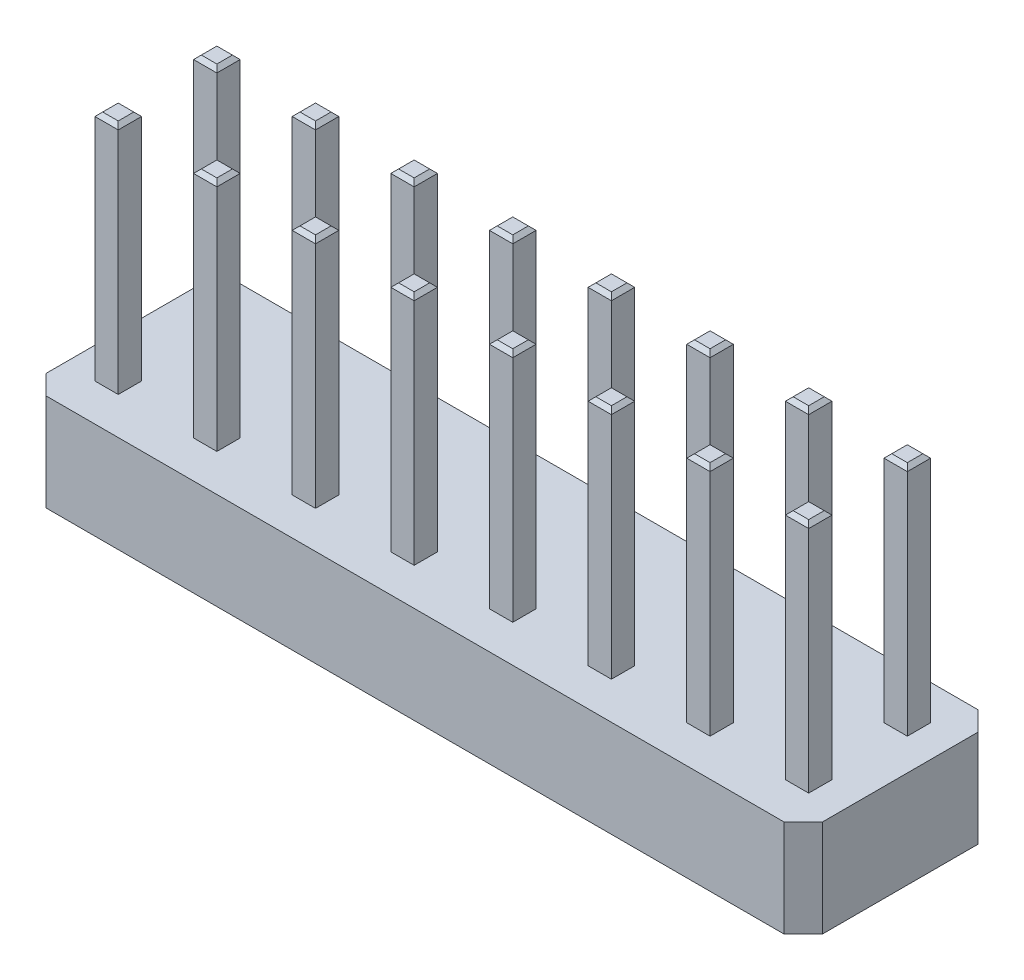
SolidWorks part; units mm, degrees
ref_plane "Plan de face" through (0, 0, 0) normal (0, 0, 1) x (1, 0, 0)
ref_plane "Plan de dessus" through (0, 0, 0) normal (0, 1, 0) x (1, 0, 0)
ref_plane "Plan de droite" through (0, 0, 0) normal (1, 0, 0) x (0, 0, -1)
sketch "Esquisse1" plane through (0, 0, 0) normal (0, 1, 0) x (1, 0, 0)
  line L1 (0, 0) -> (20, 0)
  line L2 (0, 0) -> (0, -5)
  line L3 (0, -5) -> (20, -5)
  line L4 (20, 0) -> (20, -5)
  dimension "D1" = 20
  dimension "D2" = 5
extrude "Boss.-Extru.1" add sketch "Esquisse1" along normal blind 2.5
sketch "Esquisse2" plane through (0, 2.5, 0) normal (0, 1, 0) x (1, 0, 0)
  line L0 (20, 0) -> (0, 0) construction
  line L1 (0.8, -0.9) -> (1.4, -0.9)
  line L2 (0.8, -0.9) -> (0.8, -1.5)
  line L3 (0.8, -1.5) -> (1.4, -1.5)
  line L4 (1.4, -0.9) -> (1.4, -1.5)
  line L5 (0.8, -3.44) -> (1.4, -3.44)
  line L6 (0.8, -3.44) -> (0.8, -4.04)
  line L7 (0.8, -4.04) -> (1.4, -4.04)
  line L8 (1.4, -3.44) -> (1.4, -4.04)
  line L17 (3.34, -0.9) -> (3.94, -0.9)
  line L18 (0, 0) -> (0, -5) construction
  line L19 (3.34, -0.9) -> (3.34, -1.5)
  line L20 (3.34, -1.5) -> (3.94, -1.5)
  line L21 (3.94, -0.9) -> (3.94, -1.5)
  line L22 (3.34, -3.44) -> (3.94, -3.44)
  line L23 (3.34, -3.44) -> (3.34, -4.04)
  line L24 (3.34, -4.04) -> (3.94, -4.04)
  line L25 (3.94, -3.44) -> (3.94, -4.04)
  line L26 (5.88, -0.9) -> (6.48, -0.9)
  line L27 (5.88, -0.9) -> (5.88, -1.5)
  line L28 (5.88, -1.5) -> (6.48, -1.5)
  line L29 (6.48, -0.9) -> (6.48, -1.5)
  line L30 (5.88, -3.44) -> (6.48, -3.44)
  line L31 (5.88, -3.44) -> (5.88, -4.04)
  line L32 (5.88, -4.04) -> (6.48, -4.04)
  line L33 (6.48, -3.44) -> (6.48, -4.04)
  line L34 (8.42, -0.9) -> (9.02, -0.9)
  line L35 (8.42, -0.9) -> (8.42, -1.5)
  line L36 (8.42, -1.5) -> (9.02, -1.5)
  line L37 (9.02, -0.9) -> (9.02, -1.5)
  line L38 (8.42, -3.44) -> (9.02, -3.44)
  line L39 (8.42, -3.44) -> (8.42, -4.04)
  line L40 (8.42, -4.04) -> (9.02, -4.04)
  line L41 (9.02, -3.44) -> (9.02, -4.04)
  line L42 (10.96, -0.9) -> (11.56, -0.9)
  line L43 (10.96, -0.9) -> (10.96, -1.5)
  line L44 (10.96, -1.5) -> (11.56, -1.5)
  line L45 (11.56, -0.9) -> (11.56, -1.5)
  line L46 (10.96, -3.44) -> (11.56, -3.44)
  line L47 (10.96, -3.44) -> (10.96, -4.04)
  line L48 (10.96, -4.04) -> (11.56, -4.04)
  line L49 (11.56, -3.44) -> (11.56, -4.04)
  line L50 (13.5, -0.9) -> (14.1, -0.9)
  line L51 (13.5, -0.9) -> (13.5, -1.5)
  line L52 (13.5, -1.5) -> (14.1, -1.5)
  line L53 (14.1, -0.9) -> (14.1, -1.5)
  line L54 (13.5, -3.44) -> (14.1, -3.44)
  line L55 (13.5, -3.44) -> (13.5, -4.04)
  line L56 (13.5, -4.04) -> (14.1, -4.04)
  line L57 (14.1, -3.44) -> (14.1, -4.04)
  line L58 (16.04, -0.9) -> (16.64, -0.9)
  line L59 (16.04, -0.9) -> (16.04, -1.5)
  line L60 (16.04, -1.5) -> (16.64, -1.5)
  line L61 (16.64, -0.9) -> (16.64, -1.5)
  line L62 (16.04, -3.44) -> (16.64, -3.44)
  line L63 (16.04, -3.44) -> (16.04, -4.04)
  line L64 (16.04, -4.04) -> (16.64, -4.04)
  line L65 (16.64, -3.44) -> (16.64, -4.04)
  line L66 (18.58, -0.9) -> (19.18, -0.9)
  line L67 (18.58, -0.9) -> (18.58, -1.5)
  line L68 (18.58, -1.5) -> (19.18, -1.5)
  line L69 (19.18, -0.9) -> (19.18, -1.5)
  line L70 (18.58, -3.44) -> (19.18, -3.44)
  line L71 (18.58, -3.44) -> (18.58, -4.04)
  line L72 (18.58, -4.04) -> (19.18, -4.04)
  line L73 (19.18, -3.44) -> (19.18, -4.04)
  dimension "D1" = 0.6
  dimension "D2" = 0.9
  dimension "D3" = 8
  dimension "D4" = 0.8
  dimension "D5" = 2.54
extrude "Boss.-Extru.2" add sketch "Esquisse2" along normal blind 6
chamfer "Chanfrein1" distance 0.1 angle 45 64 edges at (16.34, 8.5, 3.44) (16.64, 8.5, 3.74) (16.34, 8.5, 4.04) (16.04, 8.5, 3.74) (18.88, 8.5, 3.44) (19.18, 8.5, 3.74) (18.88, 8.5, 4.04) (18.58, 8.5, 3.74) (18.88, 8.5, 0.9) (19.18, 8.5, 1.2) (18.88, 8.5, 1.5) (18.58, 8.5, 1.2) (16.34, 8.5, 0.9) (16.64, 8.5, 1.2) (16.34, 8.5, 1.5) (16.04, 8.5, 1.2) (13.8, 8.5, 3.44) (14.1, 8.5, 3.74) (13.8, 8.5, 4.04) (13.5, 8.5, 3.74) (13.8, 8.5, 0.9) (14.1, 8.5, 1.2) (13.8, 8.5, 1.5) (13.5, 8.5, 1.2) (11.26, 8.5, 3.44) (11.56, 8.5, 3.74) (11.26, 8.5, 4.04) (10.96, 8.5, 3.74) (11.26, 8.5, 0.9) (11.56, 8.5, 1.2) (11.26, 8.5, 1.5) (10.96, 8.5, 1.2) (8.72, 8.5, 3.44) (9.02, 8.5, 3.74) (8.72, 8.5, 4.04) (8.42, 8.5, 3.74) (8.72, 8.5, 0.9) (9.02, 8.5, 1.2) (8.72, 8.5, 1.5) (8.42, 8.5, 1.2) (6.18, 8.5, 3.44) (6.48, 8.5, 3.74) (6.18, 8.5, 4.04) (5.88, 8.5, 3.74) (6.18, 8.5, 0.9) (6.48, 8.5, 1.2) (6.18, 8.5, 1.5) (5.88, 8.5, 1.2) (3.64, 8.5, 3.44) (3.94, 8.5, 3.74) (3.64, 8.5, 4.04) (3.34, 8.5, 3.74) (3.64, 8.5, 0.9) (3.94, 8.5, 1.2) (3.64, 8.5, 1.5) (3.34, 8.5, 1.2) (1.1, 8.5, 3.44) (1.4, 8.5, 3.74) (1.1, 8.5, 4.04) (0.8, 8.5, 3.74) (1.1, 8.5, 0.9) (1.4, 8.5, 1.2) (1.1, 8.5, 1.5) (0.8, 8.5, 1.2)
chamfer "Chanfrein2" distance 0.5 angle 45 4 edges at (20, 1.25, 5) (20, 1.25, 0) (0, 1.25, 0) (0, 1.25, 5)
